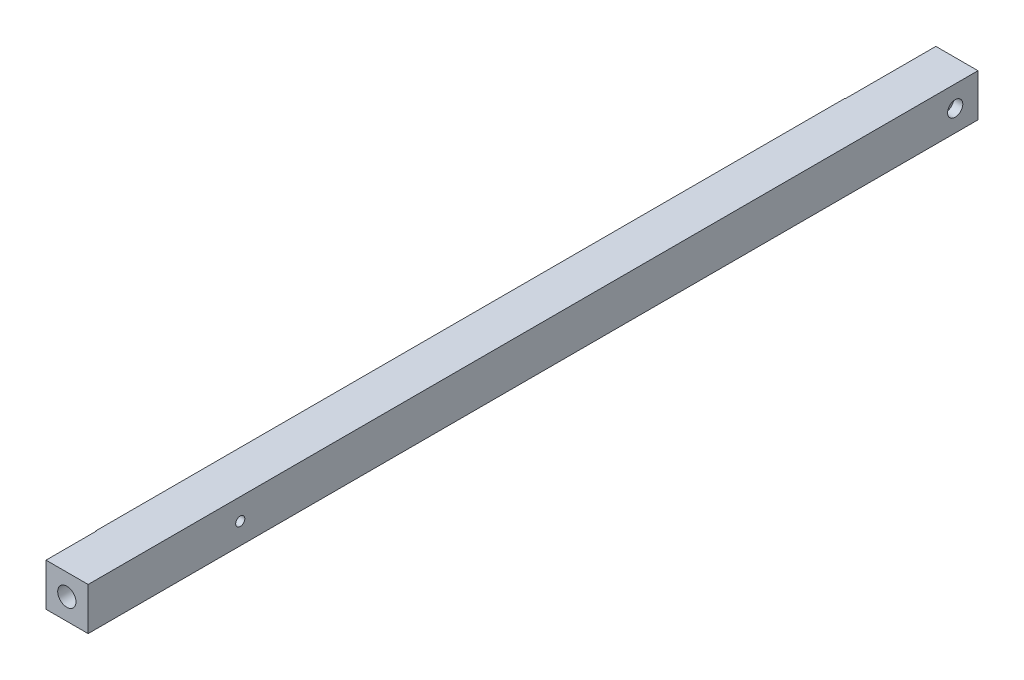
SolidWorks part; units mm, degrees
ref_plane "Ön Düzlem" through (0, 0, 0) normal (0, 0, 1) x (1, 0, 0)
ref_plane "Üst Düzlem" through (0, 0, 0) normal (0, 1, 0) x (1, 0, 0)
ref_plane "Sağ Düzlem" through (0, 0, 0) normal (1, 0, 0) x (0, 0, -1)
sketch "Çizim1" plane through (0, 0, 0) normal (0, 0, 1) x (1, 0, 0)
  line L1 (-14, -14) -> (14, -14)
  line L2 (-14, -14) -> (-14, 14)
  line L3 (-14, 14) -> (14, 14)
  line L4 (14, -14) -> (14, 14)
  line L5 (-14, -14) -> (14, 14) construction
  line L6 (-14, 14) -> (14, -14) construction
  point P0 (0, 0)
  dimension "D1" = 28
  dimension "D2" = 28
extrude "Yükseklik-Ekstrüzyon1" add sketch "Çizim1" along normal blind 585
sketch "Çizim2" plane through (0, 0, 585) normal (0, 0, 1) x (1, 0, 0)
  circle A0 centre (0, 0) radius 6
  dimension "D1" = 12
extrude "Kes-Ekstrüzyon1" cut sketch "Çizim2" against normal blind 60
sketch "Sketch1" plane through (0, 0, 0) normal (0, 0, -1) x (-1, 0, 0)
  line L0 (-14, -14) -> (-14, 14) construction
  line L1 (-14, 14) -> (14, 14) construction
  line L2 (14, 14) -> (14, -14) construction
  line L3 (14, -14) -> (-14, -14) construction
  circle A0 centre (-7, 7) radius 3.5
  circle A1 centre (7, -7) radius 3.5
  dimension "D1" = 7
  dimension "D5" = 7
  dimension "D2" = 7
  dimension "D3" = 7
  dimension "D4" = 7
extrude "Cut-Extrude1" cut sketch "Sketch1" against normal blind 25
sketch "Sketch3" plane through (-14, 0, 0) normal (-1, 0, 0) x (0, 0, 1)
  line L0 (585, 14) -> (0, 14) construction
  line L1 (585, 14) -> (585, -14) construction
  circle A0 centre (485, 0) radius 3
  dimension "D1" = 6
  dimension "D3" = 100
  dimension "D2" = 14
extrude "Cut-Extrude2" cut sketch "Sketch3" against normal through all
sketch "Sketch5" plane through (-14, 0, 0) normal (-1, 0, 0) x (0, 0, 1)
  circle A0 centre (485, 0) radius 4.25
  dimension "D1" = 8.5
extrude "Cut-Extrude4" cut sketch "Sketch5" against normal blind 6
sketch "Sketch6" plane through (-14, 0, 0) normal (-1, 0, 0) x (0, 0, 1)
  line L0 (585, 14) -> (585, -14) construction
  line L1 (552, -90.7245) -> (620.7914, -90.7245)
  line L2 (552, -90.7245) -> (552, 128.4822)
  line L3 (552, 128.4822) -> (620.7914, 128.4822)
  line L4 (620.7914, -90.7245) -> (620.7914, 128.4822)
  line L5 (-9.4879, -79.8046) -> (59.5, -79.8046)
  line L6 (-9.4879, -79.8046) -> (-9.4879, 95.1359)
  line L7 (-9.4879, 95.1359) -> (59.5, 95.1359)
  line L8 (59.5, -79.8046) -> (59.5, 95.1359)
  line L9 (0, 14) -> (0, -14) construction
  dimension "D1" = 33
  dimension "D2" = 59.5
extrude "Cut-Extrude5" cut sketch "Sketch6" against normal blind 0.3
sketch "Sketch7" plane through (14, 0, 0) normal (1, 0, 0) x (0, 0, -1)
  line L0 (0, 0) -> (-66.8782, 0) construction
  line L1 (0, -14) -> (0, 14) construction
  circle A0 centre (-15, 0) radius 3
  dimension "D1" = 15
  dimension "D2" = 6
extrude "Cut-Extrude6" cut sketch "Sketch7" against normal blind 84
sketch "Sketch8" plane through (14, 0, 0) normal (1, 0, 0) x (0, 0, -1)
  circle A0 centre (-15, 0) radius 5
  dimension "D1" = 10
extrude "Cut-Extrude7" cut sketch "Sketch8" against normal blind 6
